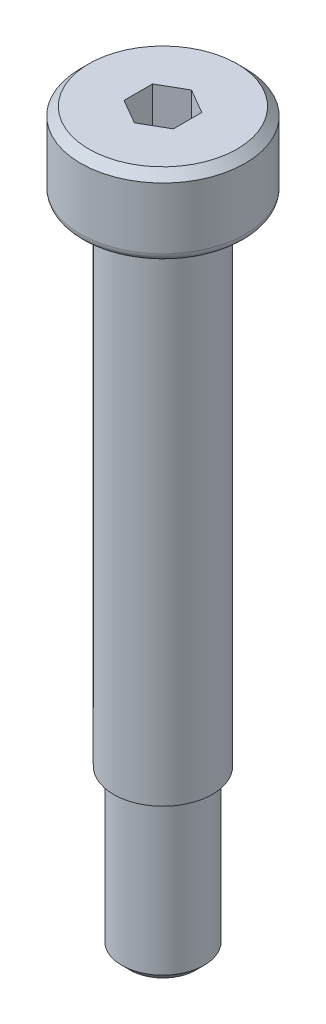
SolidWorks part; units mm, degrees
material "Plain Carbon Steel"
ref_plane "Front Plane" through (0, 0, 0) normal (0, 0, 1) x (1, 0, 0)
ref_plane "Top Plane" through (0, 0, 0) normal (0, 1, 0) x (1, 0, 0)
ref_plane "Right Plane" through (0, 0, 0) normal (1, 0, 0) x (0, 0, -1)
sketch "Sketch1" plane through (0, 0, 0) normal (0, 0, 1) x (1, 0, 0)
  line L0 (0, 0) -> (5, 0)
  line L1 (5, 0) -> (5, -4.73)
  line L2 (5, -4.73) -> (2.75, -4.73)
  line L3 (2.75, -4.73) -> (2.75, -5.23)
  line L4 (2.75, -5.23) -> (3, -5.23)
  line L5 (3, -5.23) -> (3, -34.73)
  line L6 (3, -34.73) -> (2.5, -34.73)
  line L7 (2.5, -34.73) -> (2.5, -44.48)
  line L8 (2.5, -44.48) -> (0, -44.48)
  line L9 (0, -44.48) -> (0, 0)
  line L10 (0, 5) -> (0, -49.48) construction
  point P13 (0, 0)
  point P14 (0, 0)
  dimension "D1" = 5
  dimension "D2" = 5
  dimension "D3" = 5
  dimension "D4" = 6
  dimension "D5" = 0.25
  dimension "D6" = 10
  dimension "D7" = 30
  dimension "D8" = 4.73
  dimension "D9" = 0.5
  dimension "D10" = 9.75
revolve "Revolve1" add sketch "Sketch1" angle 360 about L10
sketch "Sketch2" plane through (0, 0, 0) normal (0, 1, 0) x (1, 0, 0)
  line L1 (0, -1.7321) -> (1.5, -0.866)
  line L2 (1.5, -0.866) -> (1.5, 0.866)
  line L3 (1.5, 0.866) -> (0, 1.7321)
  line L4 (0, 1.7321) -> (-1.5, 0.866)
  line L5 (-1.5, 0.866) -> (-1.5, -0.866)
  line L6 (-1.5, -0.866) -> (0, -1.7321)
  circle A0 centre (0, 0) radius 1.5 construction
  point P1 (0, 0)
  dimension "D1" = 3
extrude "Cut-Extrude1" cut sketch "Sketch2" against normal blind 2.4
chamfer "Chamfer1" distance 0.5 angle 45 1 edges at (-5, 0, 0)
fillet "Fillet1" radius 0.5 1 edges at (-5, -4.73, 0)
chamfer "Chamfer2" distance 0.5 angle 45 1 edges at (-2.5, -44.48, 0)
